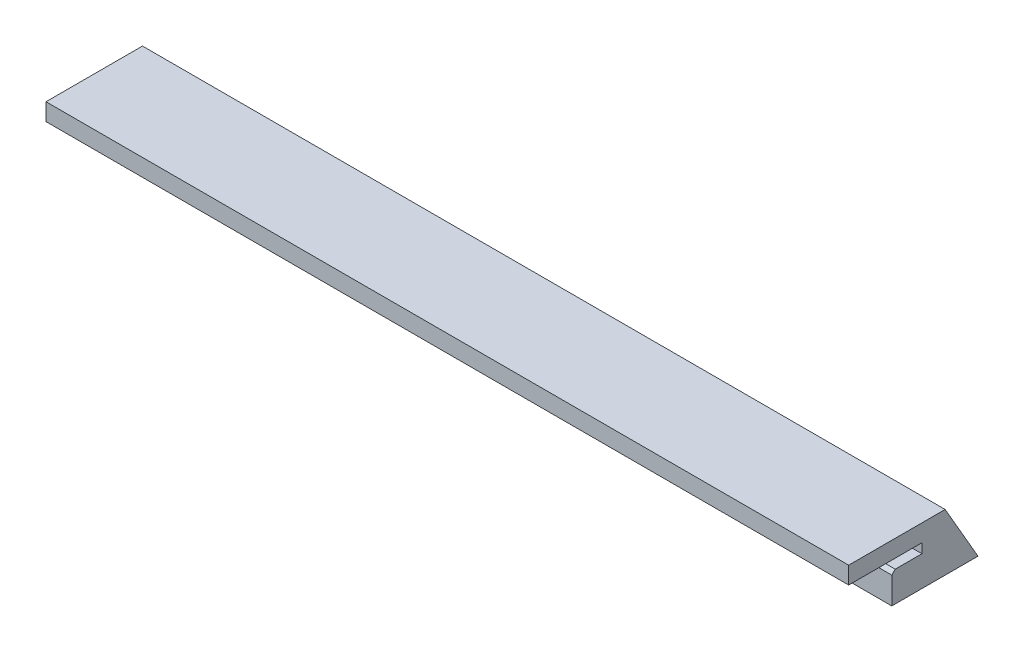
SolidWorks part; units mm, degrees
ref_plane "前视基准面" through (0, 0, 0) normal (0, 0, 1) x (1, 0, 0)
ref_plane "上视基准面" through (0, 0, 0) normal (0, 1, 0) x (1, 0, 0)
ref_plane "右视基准面" through (0, 0, 0) normal (1, 0, 0) x (0, 0, -1)
other "Configuration Table"
sketch "草图2" plane through (0, 0, 0) normal (0, 1, 0) x (1, 0, 0)
  line L1 (0, 0) -> (93.1, 0)
  line L2 (0, 0) -> (0, 10)
  line L3 (0, 10) -> (93.1, 10)
  line L4 (93.1, 0) -> (93.1, 10)
  dimension "D1" = 93.1
  dimension "D2" = 10
extrude "凸台-拉伸1" add sketch "草图2" along normal blind 3.5
sketch "草图4" plane through (0, 3.5, 0) normal (0, 1, 0) x (1, 0, 0)
  line L0 (93.1, 0) -> (93.1, 10) construction
  line L1 (0, 10) -> (93.1, 10)
  line L2 (0, 10) -> (0, 3.5)
  line L3 (0, 3.5) -> (93.1, 3.5)
  line L4 (93.1, 10) -> (93.1, 3.5)
  dimension "D1" = 6.5
extrude "凸台-拉伸2" add sketch "草图4" along normal blind 1.1
sketch "草图5" plane through (0, 4.6, 0) normal (0, 1, 0) x (1, 0, 0)
  line L0 (93.1, 3.5) -> (93.1, 10) construction
  line L1 (0, 10) -> (93.1, 10)
  line L2 (0, 10) -> (0, 0)
  line L3 (0, 0) -> (93.1, 0)
  line L4 (93.1, 10) -> (93.1, 0)
  point P4 (93.1, 9)
  dimension "D1" = 10
extrude "凸台-拉伸3" add sketch "草图5" along normal blind 2
sketch "草图6" plane through (0, 0, 0) normal (-1, 0, 0) x (0, 0, 1)
  line L0 (-10, 0) -> (-6.1895, 6.6)
  line L1 (-10, 0) -> (0, 0) construction
  line L2 (-10, 6.6) -> (-10, 0) construction
  line L3 (-10, 6.6) -> (0, 6.6) construction
  line L4 (-6.1895, 6.6) -> (-10, 6.6)
  line L5 (-10, 6.6) -> (-10, 0)
  dimension "D1" = 30
extrude "切除-拉伸1" cut sketch "草图6" against normal through all
sketch "草图7" plane through (0, 0, -3.5) normal (0, 0, 1) x (1, 0, 0)
  line L0 (0, 4.6) -> (93.1, 4.6) construction
  line L1 (5, 4.6) -> (88.1, 4.6)
  line L2 (5, 4.6) -> (5, 3.5)
  line L3 (5, 3.5) -> (88.1, 3.5)
  line L4 (88.1, 4.6) -> (88.1, 3.5)
  line L5 (0, 3.5) -> (93.1, 3.5) construction
  line L6 (0, 4.6) -> (0, 3.5) construction
  line L7 (93.1, 4.6) -> (93.1, 3.5) construction
  dimension "D1" = 5
  dimension "D2" = 5
extrude "凸台-拉伸4" add sketch "草图7" along normal up to surface (3.5 mm away) up to face at (46.55, 1.75, 0)
chamfer "倒角1" distance 0.4 angle 45 2 edges at (2.5, 3.5, 0) (90.6, 3.5, 0)
sketch "草图8" plane through (0, 0, 0) normal (0, -1, 0) x (1, 0, 0)
  line L0 (46.55, 147) -> (46.55, 0) construction
  line L1 (0, 0) -> (93.1, 0) construction
  line L2 (5, 0) -> (0, 0) construction
  circle A0 centre (46.55, 147) radius 150
  dimension "D1" = 300
  dimension "D2" = 147
extrude "切除-拉伸2" cut sketch "草图8" against normal up to next
sketch "草图9" plane through (0, 0, 0) normal (0, 0, 1) x (1, 0, 0)
  line L1 (0, 4.6) -> (93.1, 4.6)
  line L2 (0, 4.6) -> (0, 6.6)
  line L3 (0, 6.6) -> (93.1, 6.6)
  line L4 (93.1, 4.6) -> (93.1, 6.6)
extrude "凸台-拉伸5" add sketch "草图9" along normal blind 5 and the other way up to next
